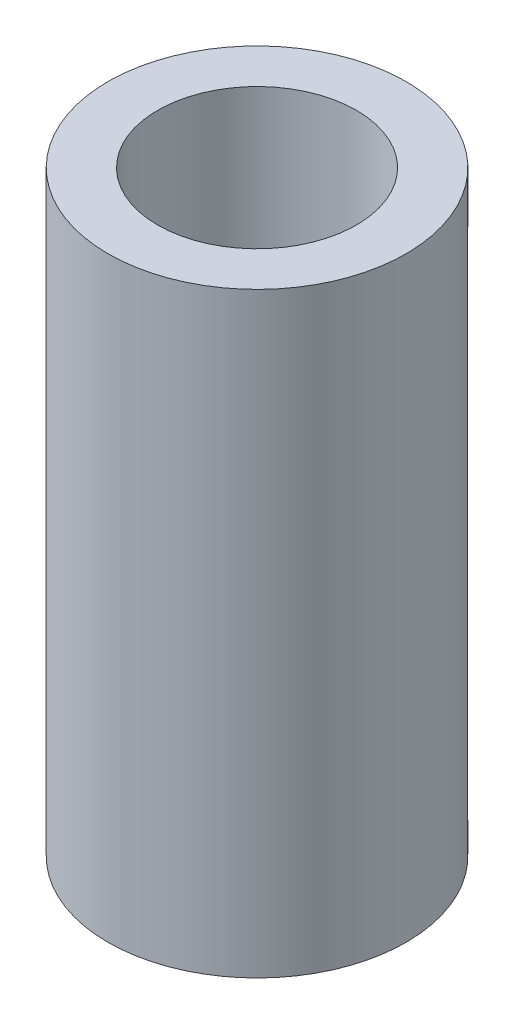
SolidWorks part; units mm, degrees
ref_plane "前视基准面" through (0, 0, 0) normal (0, 0, 1) x (1, 0, 0)
ref_plane "上视基准面" through (0, 0, 0) normal (0, 1, 0) x (1, 0, 0)
ref_plane "右视基准面" through (0, 0, 0) normal (1, 0, 0) x (0, 0, -1)
sketch "草图1" plane through (0, 0, 0) normal (0, 1, 0) x (1, 0, 0)
  circle A0 centre (0, 0) radius 4.5
  circle A1 centre (0, 0) radius 3
  dimension "D1" = 6
  dimension "D2" = 9
extrude "凸台-拉伸1" add sketch "草图1" along normal blind 18
sketch "草图2" plane through (0, 0, 0) normal (0, 0, 1) x (1, 0, 0)
  line L0 (-4.5, 0) -> (4.5, 0) construction
  circle A0 centre (0, 6) radius 3
  dimension "D1" = 6
  dimension "D2" = 6
extrude "切除-拉伸1" cut sketch "草图2" against normal through all
